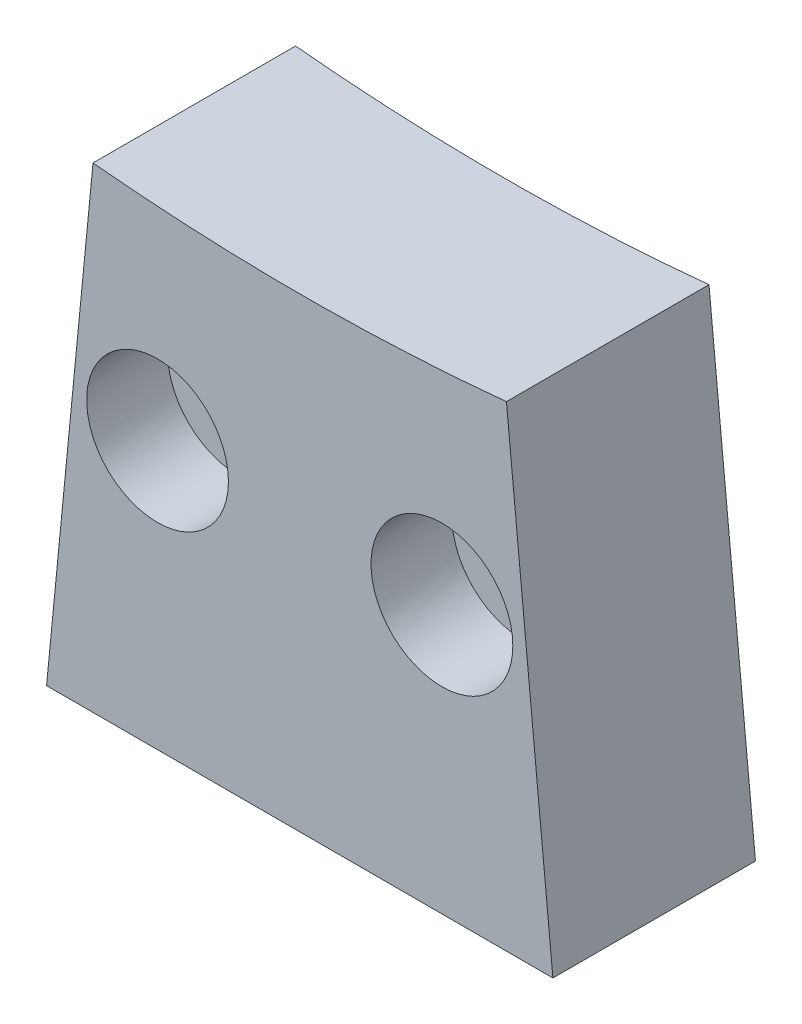
SolidWorks part; units mm, degrees
ref_plane "Plan de face" through (0, 0, 0) normal (0, 0, 1) x (1, 0, 0)
ref_plane "Plan de dessus" through (0, 0, 0) normal (0, 1, 0) x (1, 0, 0)
ref_plane "Plan de droite" through (0, 0, 0) normal (1, 0, 0) x (0, 0, -1)
sketch "Esquisse1" plane through (0, 0, 0) normal (0, 0, 1) x (1, 0, 0)
  line L0 (0, 0) -> (0, -128) construction
  line L1 (0, 0) -> (-10.2054, -104.5029) construction
  line L2 (0, 0) -> (10.2054, -104.5029) construction
  line L3 (-12.5, -128) -> (12.5, -128)
  line L4 (-10.2054, -104.5029) -> (-12.5, -128)
  line L5 (10.2054, -104.5029) -> (12.5, -128)
  arc A1 (10.2054, -104.5029) -> (-10.2054, -104.5029) centre (0, 0) cw
  point P1 (0, -105)
  point P8 (0, -128)
  dimension "D1" = 105
  dimension "D2" = 128
  dimension "D3" = 25
extrude "Boss.-Extru.1" add sketch "Esquisse1" along normal blind 10
sketch "Esquisse2" plane through (0, -128, 0) normal (0, -1, 0) x (1, 0, 0)
  line L0 (-4.75, 6) -> (4.75, 6) construction
  line L1 (-12.5, 10) -> (12.5, 10) construction
  circle A0 centre (-4.75, 6) radius 1.025
  circle A1 centre (4.75, 6) radius 1.025
  point P4 (0, 6)
  point P7 (0, 10)
  dimension "D1" = 2.05
  dimension "D2" = 9.5
  dimension "D3" = 4
extrude "Enlèv. mat.-Extru.1" cut sketch "Esquisse2" against normal blind 8
sketch "Esquisse3" plane through (0, 0, 10) normal (0, 0, 1) x (1, 0, 0)
  line L0 (0, -105) -> (0, -128) construction
  line L1 (-12.5, -128) -> (12.5, -128) construction
  line L2 (-7.0206, -114.7855) -> (0, 0) construction
  line L3 (0, 0) -> (7.0206, -114.7855) construction
  arc A0 (7.0206, -114.7855) -> (-7.0206, -114.7855) centre (0, 0) cw construction
  circle A1 centre (-7.0206, -114.7855) radius 1.75
  circle A2 centre (7.0206, -114.7855) radius 1.75
  arc A3 (-10.2054, -104.5029) -> (10.2054, -104.5029) centre (0, 0) ccw construction
  point P13 (0, -115)
  dimension "D1" = 115
  dimension "D2" = 3.5
  dimension "D3" = 7
extrude "Enlèv. mat.-Extru.2" cut sketch "Esquisse3" against normal up to next
sketch "Esquisse4" plane through (0, 0, 10) normal (0, 0, 1) x (1, 0, 0)
  circle A0 centre (-7.0206, -114.7855) radius 3.5
  circle A1 centre (7.0206, -114.7855) radius 3.5
  circle M4 centre (7.0206, -114.7855) radius 1.75
  dimension "D1" = 7
extrude "Enlèv. mat.-Extru.3" cut sketch "Esquisse4" against normal blind 4 contours A1 M4 | A0
